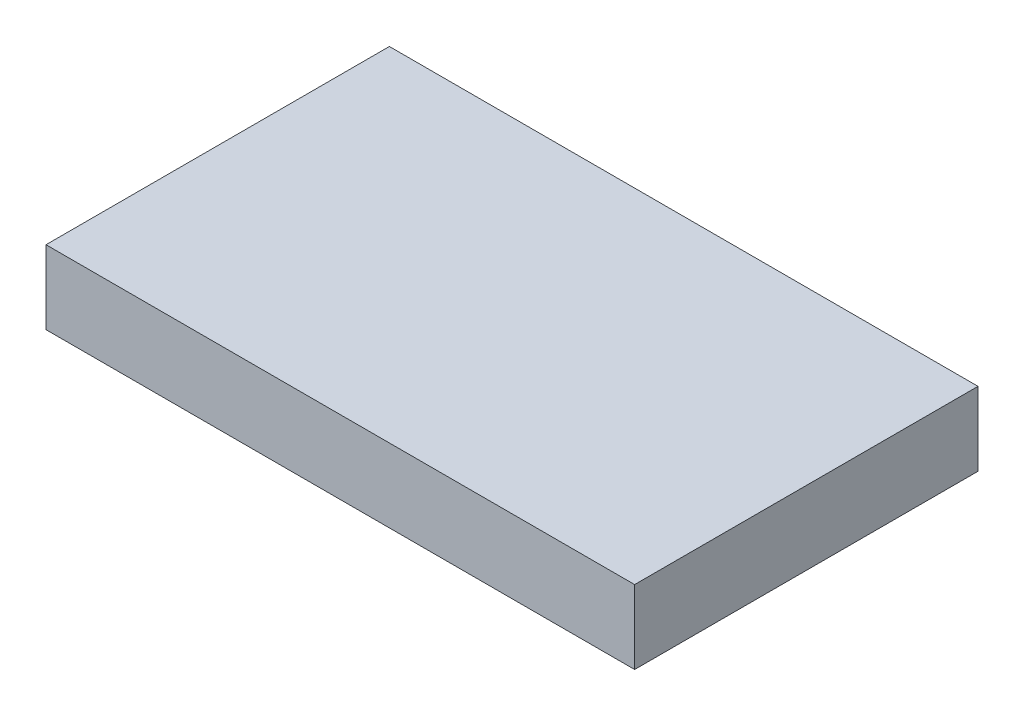
SolidWorks part; units mm, degrees
ref_plane "Front Plane" through (0, 0, 0) normal (0, 0, 1) x (1, 0, 0)
ref_plane "Top Plane" through (0, 0, 0) normal (0, 1, 0) x (1, 0, 0)
ref_plane "Right Plane" through (0, 0, 0) normal (1, 0, 0) x (0, 0, -1)
sketch "Sketch3" plane through (0, 0, 0) normal (0, 1, 0) x (1, 0, 0)
  line L1 (0, 0) -> (120, 0)
  line L2 (0, 0) -> (0, 70)
  line L3 (0, 70) -> (120, 70)
  line L4 (120, 0) -> (120, 70)
  dimension "D1" = 70
  dimension "D2" = 120
extrude "Boss-Extrude1" add sketch "Sketch3" along normal blind 15
